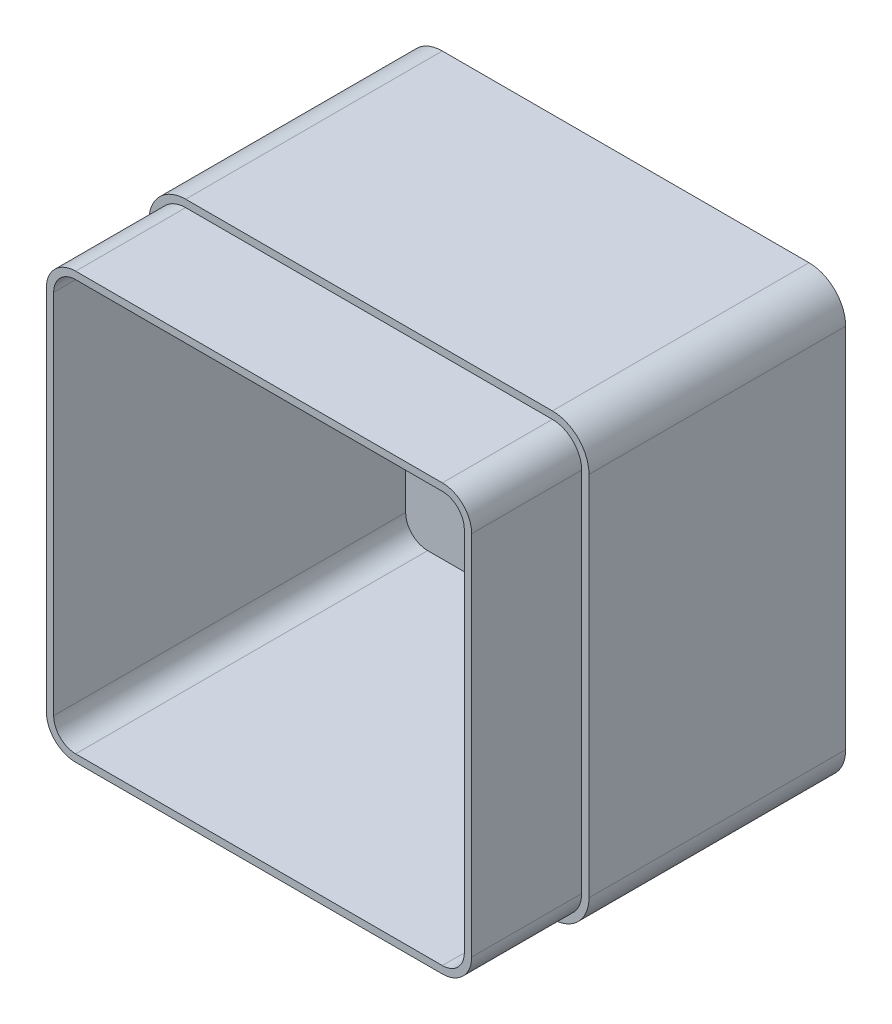
SolidWorks part; units mm, degrees
ref_plane "Front Plane" through (0, 0, 0) normal (0, 0, 1) x (1, 0, 0)
ref_plane "Top Plane" through (0, 0, 0) normal (0, 1, 0) x (1, 0, 0)
ref_plane "Right Plane" through (0, 0, 0) normal (1, 0, 0) x (0, 0, -1)
sketch "Sketch1" plane through (0, 0, 0) normal (0, 0, 1) x (1, 0, 0)
  line L1 (-60, -60) -> (60, -60)
  line L2 (-60, -60) -> (-60, 60)
  line L3 (-60, 60) -> (60, 60)
  line L4 (60, -60) -> (60, 60)
  line L5 (-60, -60) -> (60, 60) construction
  line L6 (-60, 60) -> (60, -60) construction
  point P0 (0, 0)
  dimension "D1" = 120
  dimension "D2" = 120
extrude "Boss-Extrude2" add sketch "Sketch1" along normal blind 70
fillet "Fillet1" radius 10 4 edges at (-60, -60, 35) (-60, 60, 35) (60, -60, 35) (60, 60, 35)
shell "Shell2" thickness 4
sketch "Sketch12" plane through (0, 0, 70) normal (0, 0, 1) x (1, 0, 0)
  line L0 (-58, 50) -> (-58, -50)
  line L1 (-50, -58) -> (50, -58)
  line L2 (58, -50) -> (58, 50)
  line L3 (50, 58) -> (-50, 58)
  line L4 (-60, 50) -> (-60, -50)
  line L5 (-50, -60) -> (50, -60)
  line L6 (60, -50) -> (60, 50)
  line L7 (50, 60) -> (-50, 60)
  line L8 (-60, 50) -> (-60, -50)
  line L9 (-50, -60) -> (50, -60)
  line L10 (60, -50) -> (60, 50)
  line L11 (50, 60) -> (-50, 60)
  arc A0 (-58, -50) -> (-50, -58) centre (-50, -50) ccw
  arc A1 (50, -58) -> (58, -50) centre (50, -50) ccw
  arc A2 (58, 50) -> (50, 58) centre (50, 50) ccw
  arc A3 (-50, 58) -> (-58, 50) centre (-50, 50) ccw
  arc A4 (-60, -50) -> (-50, -60) centre (-50, -50) ccw
  arc A5 (50, -60) -> (60, -50) centre (50, -50) ccw
  arc A6 (60, 50) -> (50, 60) centre (50, 50) ccw
  arc A7 (-50, 60) -> (-60, 50) centre (-50, 50) ccw
  arc A8 (-60, -50) -> (-50, -60) centre (-50, -50) ccw
  arc A9 (50, -60) -> (60, -50) centre (50, -50) ccw
  arc A10 (60, 50) -> (50, 60) centre (50, 50) ccw
  arc A11 (-50, 60) -> (-60, 50) centre (-50, 50) ccw
  dimension "D1" = 0
  dimension "D2" = 2
extrude "Boss-Extrude3" add sketch "Sketch12" along normal blind 30 contours L3 A3 L0 A0 L1 A1 L2 A2
sketch "Sketch14" plane through (0, 0, 100) normal (0, 0, 1) x (1, 0, 0)
  line L12 (50, 56) -> (-50, 56)
  line L13 (-56, 50) -> (-56, -50)
  line L14 (-50, -56) -> (50, -56)
  line L15 (56, -50) -> (56, 50)
  line L16 (50, 56) -> (-50, 56)
  line L17 (-56, 50) -> (-56, -50)
  line L18 (-50, -56) -> (50, -56)
  line L19 (56, -50) -> (56, 50)
  arc A12 (56, 50) -> (50, 56) centre (50, 50) ccw
  arc A13 (-50, 56) -> (-56, 50) centre (-50, 50) ccw
  arc A14 (-56, -50) -> (-50, -56) centre (-50, -50) ccw
  arc A15 (50, -56) -> (56, -50) centre (50, -50) ccw
  arc A16 (56, 50) -> (50, 56) centre (50, 50) ccw
  arc A17 (-50, 56) -> (-56, 50) centre (-50, 50) ccw
  arc A18 (-56, -50) -> (-50, -56) centre (-50, -50) ccw
  arc A19 (50, -56) -> (56, -50) centre (50, -50) ccw
  dimension "D1" = 2
extrude "Cut-Extrude9" cut sketch "Sketch14" against normal blind 30 contours A16 L16 A17 L17 A18 L18 A19 L19
